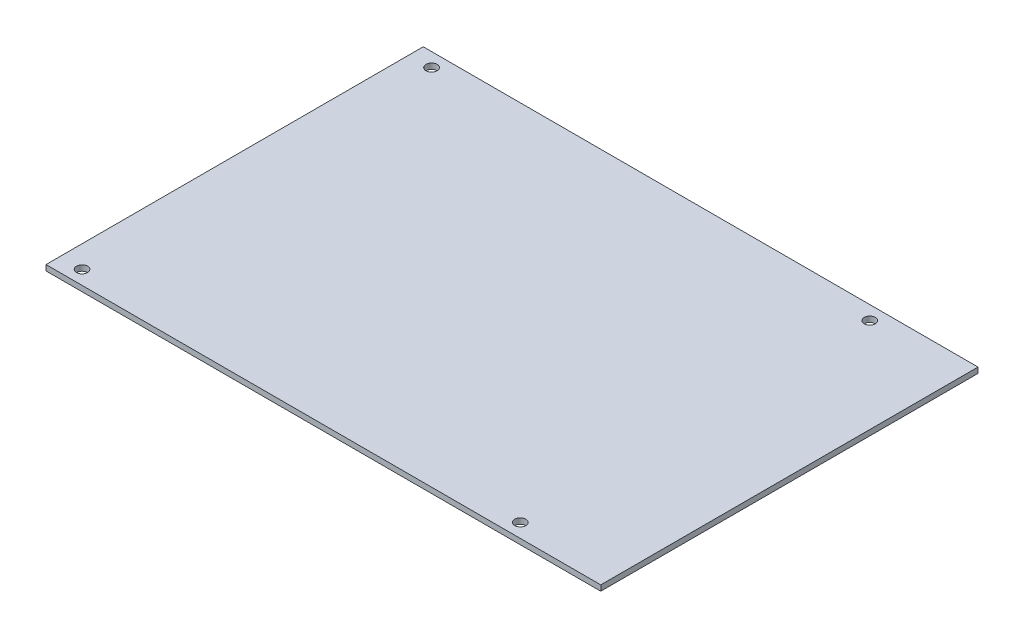
SolidWorks part; units mm, degrees
material "Плата обработки данных, простая"
ref_plane "Спереди" through (0, 0, 0) normal (0, 0, 1) x (1, 0, 0)
ref_plane "Сверху" through (0, 0, 0) normal (0, 1, 0) x (1, 0, 0)
ref_plane "Справа" through (0, 0, 0) normal (1, 0, 0) x (0, 0, -1)
sketch "Эскиз1" plane through (0, 0, 0) normal (0, 1, 0) x (1, 0, 0)
  line L1 (50, -34) -> (-50, -34)
  line L2 (50, -34) -> (50, 34)
  line L3 (50, 34) -> (-50, 34)
  line L4 (-50, -34) -> (-50, 34)
  line L5 (50, -34) -> (-50, 34) construction
  line L6 (50, 34) -> (-50, -34) construction
  point P0 (0, 0)
extrude "Бобышка-Вытянуть1" add sketch "Эскиз1" along normal blind 1
sketch "Эскиз2" plane through (0, 1, 0) normal (0, 1, 0) x (1, 0, 0)
  circle A0 centre (-46, 31.5) radius 1
  circle A1 centre (33, 31.5) radius 1
  circle A2 centre (33, -31.5) radius 1
  circle A3 centre (-46, -31.5) radius 1
extrude "Вырез-Вытянуть1" cut sketch "Эскиз2" against normal blind 10
